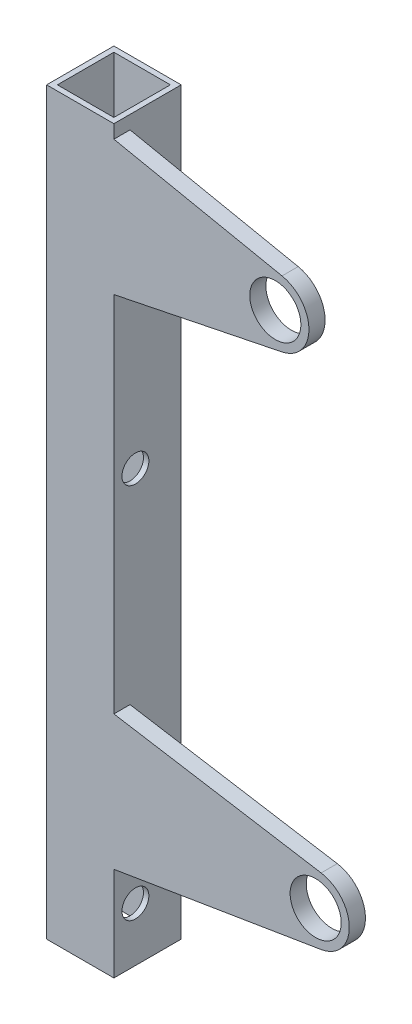
SolidWorks part; units mm, degrees
ref_plane "Front Plane" through (0, 0, 0) normal (0, 0, 1) x (1, 0, 0)
ref_plane "Top Plane" through (0, 0, 0) normal (0, 1, 0) x (1, 0, 0)
ref_plane "Right Plane" through (0, 0, 0) normal (1, 0, 0) x (0, 0, -1)
sketch "Sketch1" plane through (0, 0, 0) normal (0, 1, 0) x (1, 0, 0)
  line L0 (-10.5, 10.5) -> (10.5, 10.5)
  line L1 (-12.5, -12.5) -> (12.5, -12.5)
  line L2 (-12.5, -12.5) -> (-12.5, 12.5)
  line L3 (-12.5, 12.5) -> (12.5, 12.5)
  line L4 (12.5, -12.5) -> (12.5, 12.5)
  line L5 (-12.5, -12.5) -> (12.5, 12.5) construction
  line L6 (-12.5, 12.5) -> (12.5, -12.5) construction
  line L7 (10.5, -10.5) -> (10.5, 10.5)
  line L8 (-10.5, -10.5) -> (10.5, -10.5)
  line L9 (-10.5, -10.5) -> (-10.5, 10.5)
  point P0 (0, 0)
  dimension "D1" = 25
  dimension "D2" = 25
  dimension "D3" = 2
extrude "Boss-Extrude1" add sketch "Sketch1" against normal blind 275
sketch "Sketch2" plane through (0, 0, 12.5) normal (0, 0, 1) x (1, 0, 0)
  line L0 (12.5, -275) -> (12.5, 0) construction
  line L1 (74.999, -17.7524) -> (12.5, -5)
  line L2 (74.999, -42.2476) -> (12.5, -55)
  line L3 (12.5, -5) -> (12.5, -55)
  line L4 (72.5, -30) -> (43.2662, -30) construction
  line L5 (-12.5, 0) -> (12.5, 0) construction
  line L6 (89.5281, -202.6656) -> (12.5, -190)
  line L7 (89.5281, -227.3344) -> (12.5, -240)
  line L8 (12.5, -240) -> (12.5, -190)
  line L9 (87.5, -215) -> (52.6414, -215) construction
  circle A0 centre (72.5, -30) radius 9.5
  arc A1 (74.999, -42.2476) -> (74.999, -17.7524) centre (72.5, -30) ccw
  circle A2 centre (87.5, -215) radius 9.5
  arc A3 (89.5281, -227.3344) -> (89.5281, -202.6656) centre (87.5, -215) ccw
  dimension "D1" = 19
  dimension "D2" = 25
  dimension "D6" = 25
  dimension "D7" = 19
  dimension "D8" = 75
  dimension "D9" = 185
  dimension "D3" = 60
  dimension "D4" = 5
  dimension "D5" = 50
  dimension "D10" = 50
extrude "Boss-Extrude2" add sketch "Sketch2" against normal blind 6
sketch "Sketch3" plane through (12.5, 0, 0) normal (1, 0, 0) x (0, 0, -1)
  line L1 (-12.5, -275) -> (12.5, -275) construction
  line L2 (-12.5, -275) -> (-12.5, -240) construction
  circle A0 centre (-4.5, -115) radius 5
  circle A1 centre (-4.5, -255) radius 5
  dimension "D1" = 10
  dimension "D2" = 140
  dimension "D3" = 20
  dimension "D4" = 8
extrude "Cut-Extrude1" cut sketch "Sketch3" against normal up to surface (25 mm away) up to face at (-12.5, -137.5, 0)
